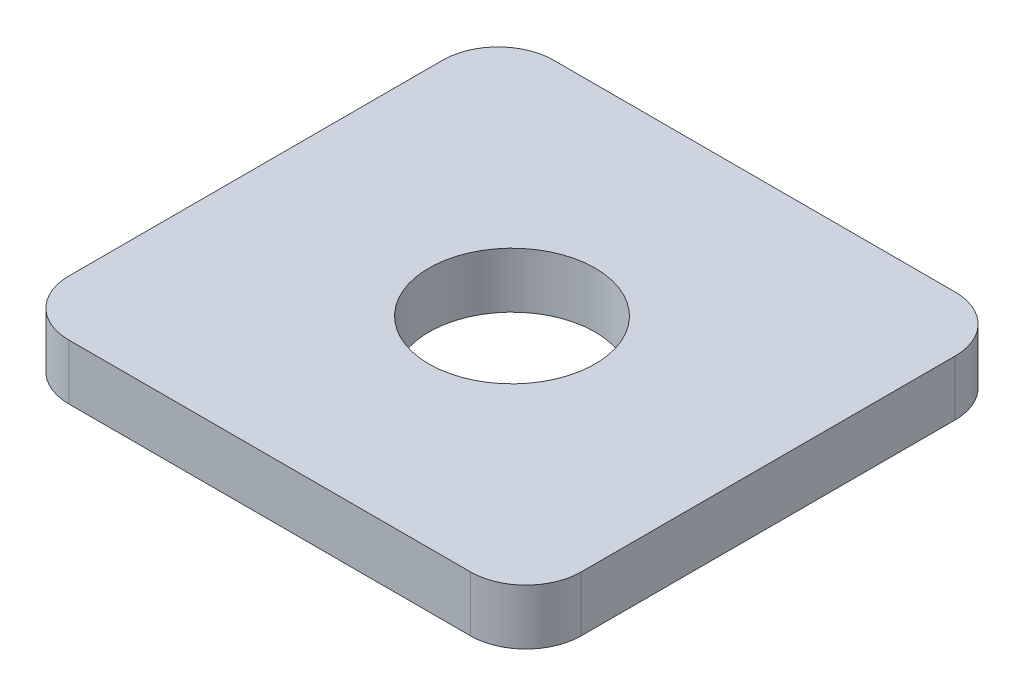
SolidWorks part; units mm, degrees
ref_plane "Front Plane" through (0, 0, 0) normal (0, 0, 1) x (1, 0, 0)
ref_plane "Top Plane" through (0, 0, 0) normal (0, 1, 0) x (1, 0, 0)
ref_plane "Right Plane" through (0, 0, 0) normal (1, 0, 0) x (0, 0, -1)
sketch "Sketch1" plane through (0, 0, 0) normal (0, 1, 0) x (1, 0, 0)
  line L1 (-9.25, -8.75) -> (9.25, -8.75)
  line L2 (-9.25, -8.75) -> (-9.25, 8.75)
  line L3 (-9.25, 8.75) -> (9.25, 8.75)
  line L4 (9.25, -8.75) -> (9.25, 8.75)
  line L5 (-9.25, -8.75) -> (9.25, 8.75) construction
  line L6 (-9.25, 8.75) -> (9.25, -8.75) construction
  point P0 (0, 0)
  dimension "D1" = 18.5
  dimension "D2" = 17.5
extrude "Boss-Extrude1" add sketch "Sketch1" along normal blind 2
fillet "Fillet1" radius 2 4 edges at (-9.25, 1, -8.75) (9.25, 1, -8.75) (9.25, 1, 8.75) (-9.25, 1, 8.75)
sketch "Sketch3" [suppressed] plane through (0, 2, 0) normal (0, 1, 0) x (1, 0, 0)
  line L0 (-7.25, -8.75) -> (7.25, -8.75) construction
  line L1 (-3.55, -8.75) -> (3.55, -8.75)
  line L2 (-3.55, -8.75) -> (-3.55, -7.75)
  line L3 (-3.55, -7.75) -> (3.55, -7.75)
  line L4 (3.55, -8.75) -> (3.55, -7.75)
  line L5 (0, 8.75) -> (0, -12.0902) construction
  line L6 (7.25, 8.75) -> (-7.25, 8.75) construction
  point P11 (0, -7.75)
  dimension "D1" = 1
  dimension "D2" = 7.1
extrude "Cut-Extrude2" [suppressed] cut sketch "Sketch3" against normal blind 10
sketch "Sketch4" plane through (0, 2, 0) normal (0, 1, 0) x (1, 0, 0)
  circle A0 centre (0, 0) radius 3
  dimension "D1" = 6
extrude "Cut-Extrude3" cut sketch "Sketch4" against normal blind 10
